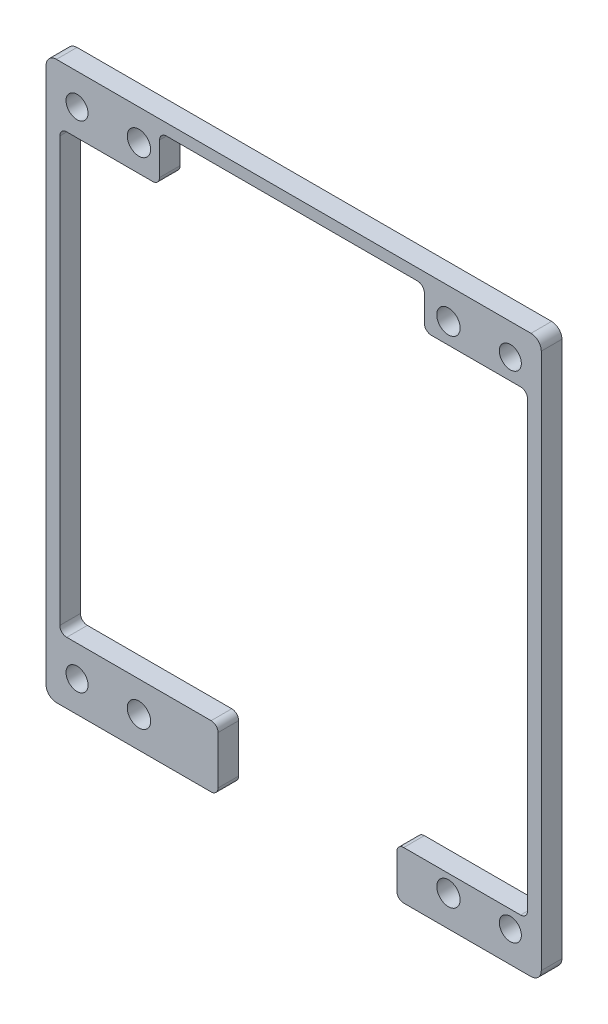
SolidWorks part; units mm, degrees
ref_plane "Alzado" through (0, 0, 0) normal (0, 0, 1) x (1, 0, 0)
ref_plane "Planta" through (0, 0, 0) normal (0, 1, 0) x (1, 0, 0)
ref_plane "Vista lateral" through (0, 0, 0) normal (1, 0, 0) x (0, 0, -1)
sketch "Model" plane through (0, 0, 0) normal (0, 0, 1) x (1, 0, 0)
  line L0 (74.6798, 300.758) -> (5.6774, 300.758)
  line L1 (76.1798, 221.2534) -> (76.1798, 299.258)
  line L2 (5.6774, 219.7534) -> (28.1772, 219.7534)
  line L3 (4.1774, 299.258) -> (4.1774, 221.2534)
  line L4 (56.1796, 219.7534) -> (74.6798, 219.7534)
  line L5 (74.1796, 292.2602) -> (74.1796, 227.7556)
  line L6 (6.1772, 291.3702) -> (6.1772, 229.73)
  line L7 (58.1796, 299.0971) -> (21.6772, 299.0971)
  line L8 (59.1796, 298.0971) -> (59.1796, 294.2602)
  line L9 (60.1796, 293.2602) -> (73.1796, 293.2602)
  line L10 (7.1772, 292.3702) -> (19.6772, 292.3702)
  line L11 (20.6772, 293.3702) -> (20.6772, 298.0971)
  line L12 (29.1772, 220.7534) -> (29.1772, 227.73)
  line L13 (28.1772, 228.73) -> (7.1772, 228.73)
  line L14 (73.1796, 226.7556) -> (56.1796, 226.7556)
  line L15 (55.1796, 220.7534) -> (55.1796, 225.7556)
  arc A0 (5.6774, 300.758) -> (4.1774, 299.258) centre (5.6774, 299.258) ccw
  arc A1 (4.1774, 221.2534) -> (5.6774, 219.7534) centre (5.6774, 221.2534) ccw
  arc A2 (74.6798, 219.7534) -> (76.1798, 221.2534) centre (74.6798, 221.2534) ccw
  arc A3 (76.1798, 299.258) -> (74.6798, 300.758) centre (74.6798, 299.258) ccw
  circle A4 centre (17.6767, 224.2531) radius 1.7
  circle A5 centre (62.6801, 224.2531) radius 1.7
  circle A6 centre (8.6771, 224.2531) radius 1.6003
  circle A7 centre (71.6798, 224.2531) radius 1.6003
  circle A8 centre (17.6767, 296.258) radius 1.7
  circle A9 centre (62.6801, 296.258) radius 1.7
  circle A10 centre (71.6798, 296.258) radius 1.6003
  circle A11 centre (8.6771, 296.258) radius 1.6003
  arc A12 (21.6772, 299.0971) -> (20.6772, 298.0971) centre (21.6772, 298.0971) ccw
  arc A13 (19.6772, 292.3702) -> (20.6772, 293.3702) centre (19.6772, 293.3702) ccw
  arc A14 (7.1772, 292.3702) -> (6.1772, 291.3702) centre (7.1772, 291.3702) ccw
  arc A15 (29.1772, 227.73) -> (28.1772, 228.73) centre (28.1772, 227.73) ccw
  arc A16 (59.1796, 298.0971) -> (58.1796, 299.0971) centre (58.1796, 298.0971) ccw
  arc A17 (59.1796, 294.2602) -> (60.1796, 293.2602) centre (60.1796, 294.2602) ccw
  arc A18 (74.1796, 292.2602) -> (73.1796, 293.2602) centre (73.1796, 292.2602) ccw
  arc A19 (56.1796, 226.7556) -> (55.1796, 225.7556) centre (56.1796, 225.7556) ccw
  arc A20 (73.1796, 226.7556) -> (74.1796, 227.7556) centre (73.1796, 227.7556) ccw
  arc A21 (28.1772, 219.7534) -> (29.1772, 220.7534) centre (28.1772, 220.7534) ccw
  arc A22 (55.1796, 220.7534) -> (56.1796, 219.7534) centre (56.1796, 220.7534) ccw
  arc A23 (6.1772, 229.73) -> (7.1772, 228.73) centre (7.1772, 229.73) ccw
extrude "Saliente-Extruir1" add sketch "Model" along normal blind 3
